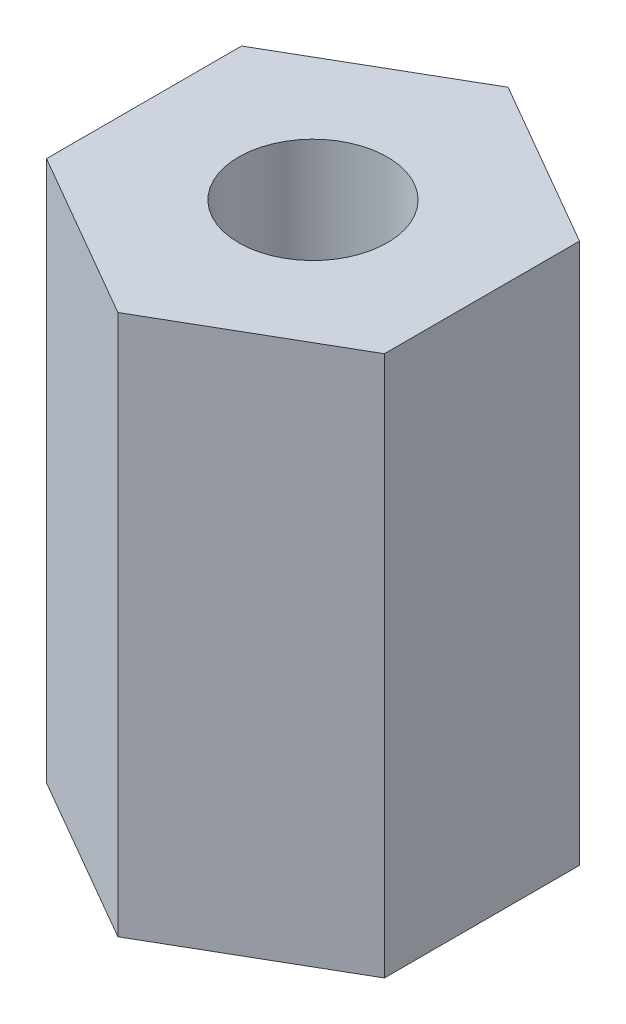
SolidWorks part; units mm, degrees
ref_plane "Front Plane" through (0, 0, 0) normal (0, 0, 1) x (1, 0, 0)
ref_plane "Top Plane" through (0, 0, 0) normal (0, 1, 0) x (1, 0, 0)
ref_plane "Right Plane" through (0, 0, 0) normal (1, 0, 0) x (0, 0, -1)
sketch "Sketch1" plane through (0, 0, 0) normal (0, 1, 0) x (1, 0, 0)
  line L1 (0, 2.8868) -> (-2.5, 1.4434)
  line L2 (-2.5, 1.4434) -> (-2.5, -1.4434)
  line L3 (-2.5, -1.4434) -> (0, -2.8868)
  line L4 (0, -2.8868) -> (2.5, -1.4434)
  line L5 (2.5, -1.4434) -> (2.5, 1.4434)
  line L6 (2.5, 1.4434) -> (0, 2.8868)
  circle A0 centre (0, 0) radius 1.1
  circle A2 centre (0, 0) radius 2.5 construction
extrude "Boss-Extrude1" add sketch "Sketch1" along normal blind 8
